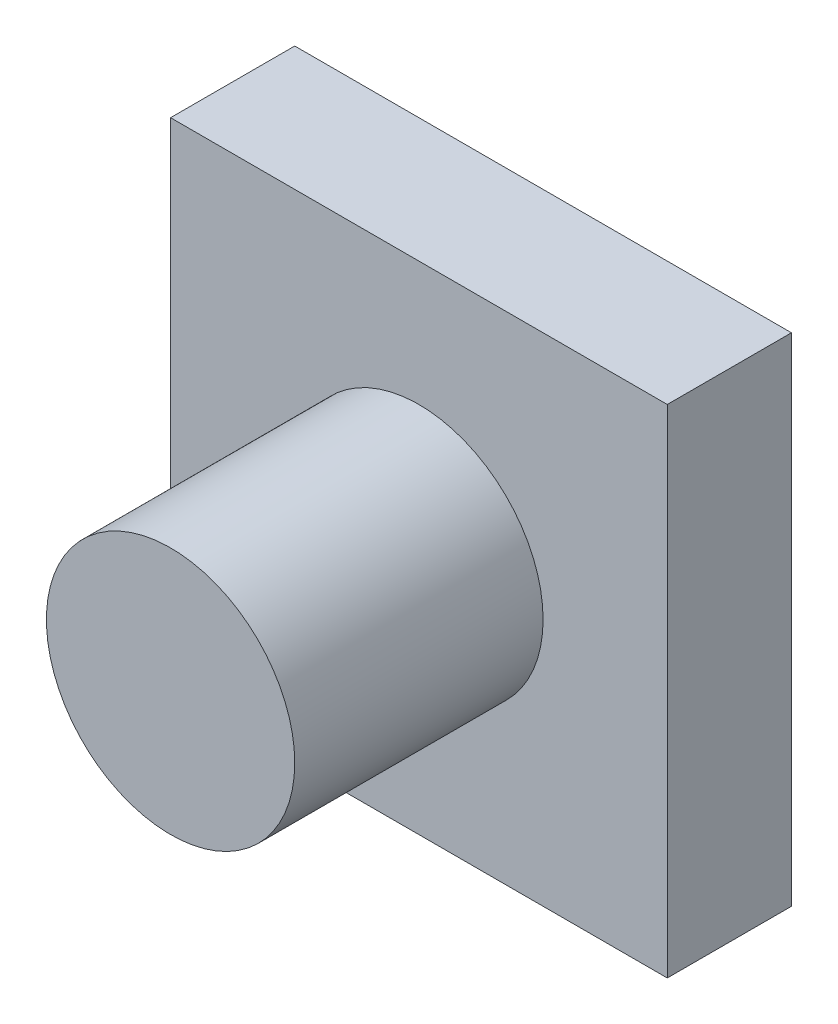
SolidWorks part; units mm, degrees
ref_plane "Front Plane" through (0, 0, 0) normal (0, 0, 1) x (1, 0, 0)
ref_plane "Top Plane" through (0, 0, 0) normal (0, 1, 0) x (1, 0, 0)
ref_plane "Right Plane" through (0, 0, 0) normal (1, 0, 0) x (0, 0, -1)
sketch "Sketch1" plane through (0, 0, 0) normal (0, 0, 1) x (1, 0, 0)
  line L1 (-20, 20) -> (20, 20)
  line L2 (-20, 20) -> (-20, -20)
  line L3 (-20, -20) -> (20, -20)
  line L4 (20, 20) -> (20, -20)
  line L5 (-20, 20) -> (20, -20) construction
  line L6 (-20, -20) -> (20, 20) construction
  point P0 (0, 0)
  dimension "D1" = 40
extrude "Boss-Extrude1" add sketch "Sketch1" along normal blind 10
sketch "Sketch2" plane through (0, 0, 10) normal (0, 0, 1) x (1, 0, 0)
  circle A0 centre (0, 0) radius 10
  dimension "D1" = 20
extrude "Boss-Extrude2" add sketch "Sketch2" along normal blind 20
